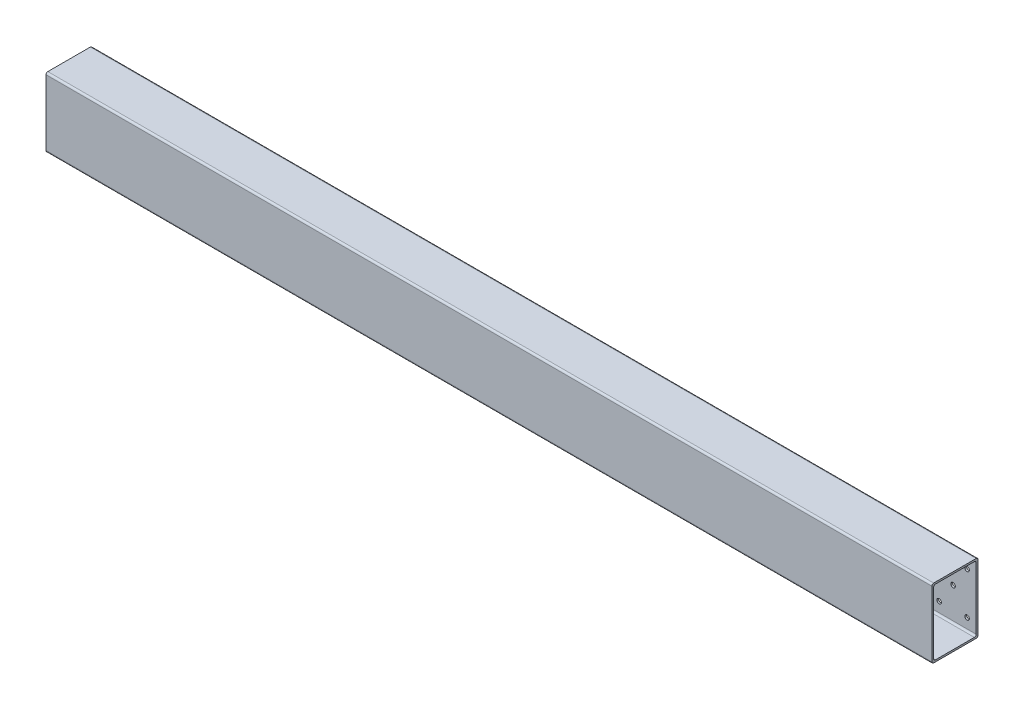
SolidWorks part; units mm, degrees
material "A500"
ref_plane "Alzado" through (0, 0, 0) normal (0, 0, 1) x (1, 0, 0)
ref_plane "Planta" through (0, 0, 0) normal (0, 1, 0) x (1, 0, 0)
ref_plane "Vista lateral" through (0, 0, 0) normal (1, 0, 0) x (0, 0, -1)
sketch "Sketch1" plane through (0, 0, 0) normal (1, 0, 0) x (0, 0, -1)
  line L1 (25.4, 38.1) -> (-25.4, 38.1)
  line L2 (25.4, 38.1) -> (25.4, -38.1)
  line L3 (25.4, -38.1) -> (-25.4, -38.1)
  line L4 (-25.4, 38.1) -> (-25.4, -38.1)
  line L5 (25.4, 38.1) -> (-25.4, -38.1) construction
  line L6 (25.4, -38.1) -> (-25.4, 38.1) construction
  point P0 (0, 0)
  dimension "D1" = 76.2
  dimension "D2" = 50.8
extrude "Boss-Extrude1" add sketch "Sketch1" against normal blind 975
sketch "Sketch2" plane through (0, 0, 0) normal (1, 0, 0) x (0, 0, -1)
  line L0 (25.4, 38.1) -> (-25.4, 38.1) construction
  line L1 (23.4, 36.1) -> (-23.4, 36.1)
  line L2 (23.4, 36.1) -> (23.4, -36.1)
  line L3 (23.4, -36.1) -> (-23.4, -36.1)
  line L4 (-23.4, 36.1) -> (-23.4, -36.1)
  line L5 (23.4, 36.1) -> (-23.4, -36.1) construction
  line L6 (23.4, -36.1) -> (-23.4, 36.1) construction
  line L7 (25.4, -38.1) -> (25.4, 38.1) construction
  point P0 (0, 0)
  dimension "D1" = 2
  dimension "D2" = 2
extrude "Cut-Extrude1" cut sketch "Sketch2" against normal through all
fillet "Fillet2" radius 2 8 edges at (-487.5, -38.1, -25.4) (-487.5, -38.1, 25.4) (-487.5, 38.1, 25.4) (-487.5, 38.1, -25.4) (-487.5, -36.1, -23.4) (-487.5, 36.1, -23.4) (-487.5, -36.1, 23.4) (-487.5, 36.1, 23.4)
sketch "Croquis1" plane through (0, 0, -25.4) normal (0, 0, -1) x (-1, 0, 0)
  line L0 (50.8, 38.1) -> (50.8, -38.1) construction
  line L1 (0, 38.1) -> (975, 38.1) construction
  line L2 (975, -38.1) -> (0, -38.1) construction
  line L3 (0, -36.1) -> (0, 36.1) construction
  line L4 (10, 38.1) -> (10, -38.1) construction
  line L5 (40.8, 38.1) -> (40.8, -38.1) construction
  line L6 (50.8, 0) -> (0, 0) construction
  circle A0 centre (25.4, 0) radius 2.5
  circle A1 centre (10, 23.1) radius 2.5
  circle A2 centre (10, -23.1) radius 2.5
  circle A3 centre (40.8, -23.1) radius 2.5
  circle A4 centre (40.8, 23.1) radius 2.5
  dimension "D4" = 5
  dimension "D5" = 5
  dimension "D6" = 5
  dimension "D7" = 5
  dimension "D8" = 5
  dimension "D1" = 50.8
  dimension "D2" = 10
  dimension "D3" = 10
  dimension "D9" = 15
  dimension "D10" = 15
  dimension "D11" = 15
  dimension "D12" = 15
extrude "Cortar-Extruir1" cut sketch "Croquis1" against normal blind 10
sketch "Croquis2" plane through (0, 0, -25.4) normal (0, 0, -1) x (-1, 0, 0)
  line L0 (924.2, 38.1) -> (924.2, -38.1) construction
  line L1 (0, 38.1) -> (975, 38.1) construction
  line L2 (975, -38.1) -> (0, -38.1) construction
  line L3 (975, -36.1) -> (975, 36.1) construction
  line L4 (924.2, 0) -> (975, 0) construction
  line L5 (934.2, 38.1) -> (934.2, -38.1) construction
  line L6 (965, 38.1) -> (965, -38.1) construction
  circle A0 centre (949.6, 0) radius 2.5
  circle A1 centre (934.2, 23.1) radius 2.5
  circle A2 centre (965, 23.1) radius 2.5
  circle A3 centre (965, -23.1) radius 2.5
  circle A4 centre (934.2, -23.1) radius 2.5
  dimension "D6" = 5
  dimension "D7" = 5
  dimension "D8" = 5
  dimension "D11" = 5
  dimension "D12" = 5
  dimension "D1" = 50.8
  dimension "D2" = 10
  dimension "D3" = 10
  dimension "D4" = 15
  dimension "D5" = 15
  dimension "D9" = 15
  dimension "D10" = 15
extrude "Cortar-Extruir2" cut sketch "Croquis2" against normal blind 10
sketch "Croquis4" plane through (0, 0, -25.4) normal (0, 0, -1) x (-1, 0, 0)
  line L0 (50.8, 38.1) -> (50.8, -38.1) construction
  line L1 (0, 38.1) -> (975, 38.1) construction
  line L2 (975, -38.1) -> (0, -38.1) construction
  line L3 (0, -36.1) -> (0, 36.1) construction
  line L4 (50.8, 0) -> (117.1896, 0) construction
  circle A0 centre (87.5, 0) radius 2.5
  dimension "D2" = 5
  dimension "D1" = 50.8
  dimension "D3" = 87.5
extrude "Cortar-Extruir3" cut sketch "Croquis4" against normal blind 10
pattern_linear "MatrizL1" count 17 spacing 50 along (-1, 0, 0) of "Cortar-Extruir3"
